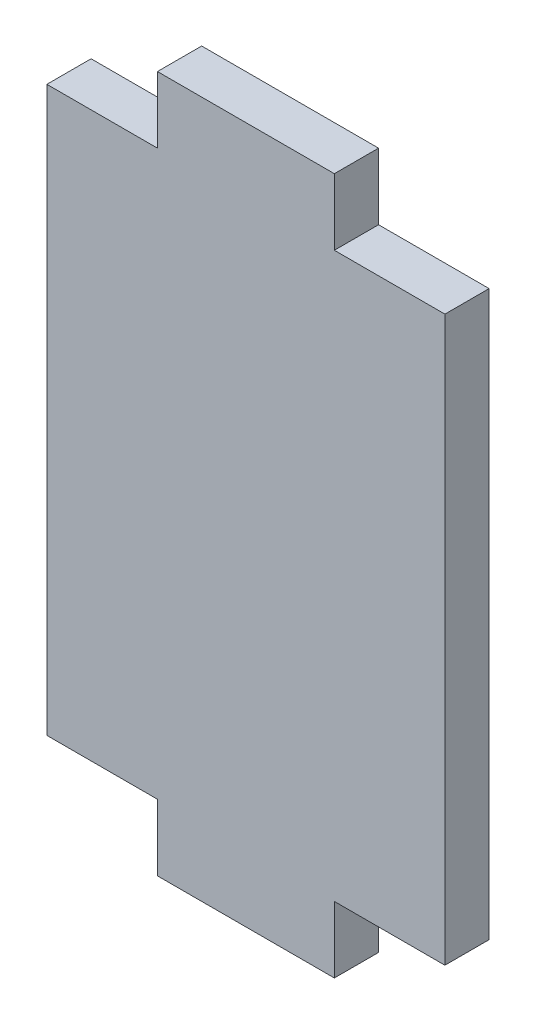
SolidWorks part; units mm, degrees
ref_plane "前视基准面" through (0, 0, 0) normal (0, 0, 1) x (1, 0, 0)
ref_plane "上视基准面" through (0, 0, 0) normal (0, 1, 0) x (1, 0, 0)
ref_plane "右视基准面" through (0, 0, 0) normal (1, 0, 0) x (0, 0, -1)
sketch "草图1" plane through (0, 0, 0) normal (0, 0, 1) x (1, 0, 0)
  line L0 (0, 0) -> (-8, 0)
  line L1 (-8, 0) -> (-8, -3)
  line L2 (-8, -3) -> (-13, -3)
  line L3 (-13, -3) -> (-13, -28.5)
  line L4 (-13, -15.75) -> (-10.3394, -15.75) construction
  line L5 (0, -3) -> (5, -3)
  line L6 (0, 0) -> (0, -3)
  line L14 (0, -31.5) -> (0, -28.5)
  line L15 (0, -28.5) -> (5, -28.5)
  line L16 (-8, -28.5) -> (-13, -28.5)
  line L17 (-8, -31.5) -> (-8, -28.5)
  line L18 (0, -31.5) -> (-8, -31.5)
  line L19 (5, -28.5) -> (5, -3)
extrude "凸台-拉伸1" add sketch "草图1" along normal blind 2
sketch "草图2" plane through (0, -3, 0) normal (0, 1, 0) x (1, 0, 0)
  line L0 (-8, -2) -> (-8, -2.1)
  line L1 (-8, -2.1) -> (0.1, -2.1)
  line L2 (0.1, -2.1) -> (0.1, 0)
